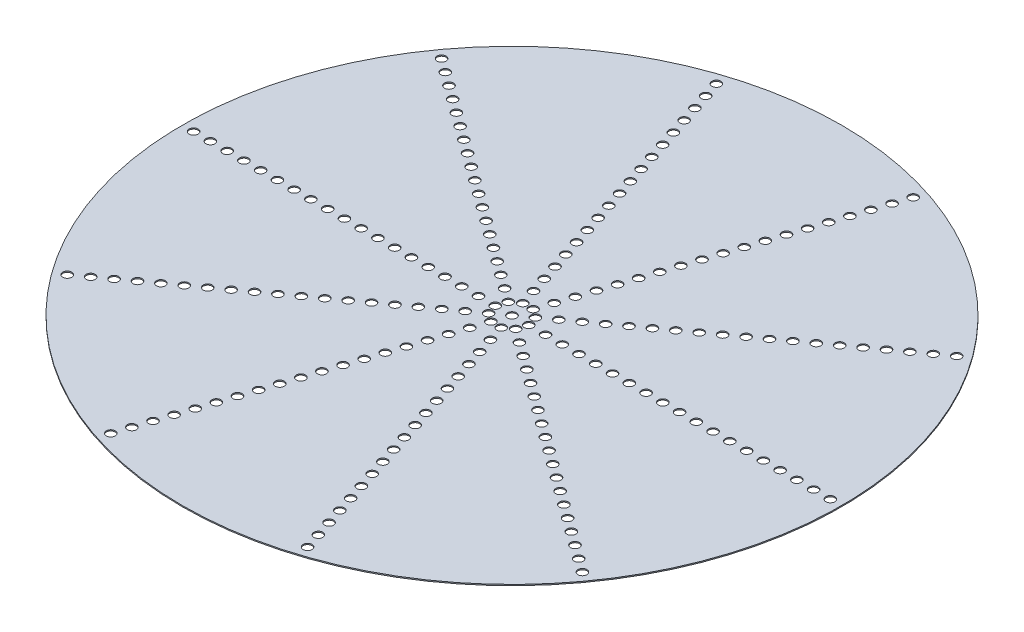
SolidWorks part; units mm, degrees
ref_plane "Front Plane" through (0, 0, 0) normal (0, 0, 1) x (1, 0, 0)
ref_plane "Top Plane" through (0, 0, 0) normal (0, 1, 0) x (1, 0, 0)
ref_plane "Right Plane" through (0, 0, 0) normal (1, 0, 0) x (0, 0, -1)
sketch "Croquis1" plane through (0, 0, 0) normal (0, 1, 0) x (1, 0, 0)
  circle A0 centre (0, 0) radius 29.5
  dimension "D1" = 59
extrude "Saliente-Extruir1" add sketch "Croquis1" along normal blind 0.1
sketch "Croquis2" plane through (0, 0.1, 0) normal (0, 1, 0) x (1, 0, 0)
  circle A0 centre (0, 0) radius 0.4
  circle A1 centre (1.5, 0) radius 0.4
  circle A2 centre (3, 0) radius 0.4
  circle A3 centre (4.5, 0) radius 0.4
  circle A4 centre (6, 0) radius 0.4
  circle A5 centre (7.5, 0) radius 0.4
  circle A6 centre (9, 0) radius 0.4
  circle A7 centre (10.5, 0) radius 0.4
  circle A8 centre (12, 0) radius 0.4
  circle A9 centre (13.5, 0) radius 0.4
  circle A10 centre (15, 0) radius 0.4
  circle A11 centre (16.5, 0) radius 0.4
  circle A12 centre (18, 0) radius 0.4
  circle A13 centre (19.5, 0) radius 0.4
  circle A14 centre (21, 0) radius 0.4
  circle A15 centre (22.5, 0) radius 0.4
  circle A16 centre (24, 0) radius 0.4
  circle A17 centre (25.5, 0) radius 0.4
  circle A18 centre (27, 0) radius 0.4
  circle A19 centre (28.5, 0) radius 0.4
  circle A20 centre (1.2135, -0.8817) radius 0.4
  circle A21 centre (2.4271, -1.7634) radius 0.4
  circle A22 centre (3.6406, -2.645) radius 0.4
  circle A23 centre (4.8541, -3.5267) radius 0.4
  circle A24 centre (6.0676, -4.4084) radius 0.4
  circle A25 centre (7.2812, -5.2901) radius 0.4
  circle A26 centre (8.4947, -6.1717) radius 0.4
  circle A27 centre (9.7082, -7.0534) radius 0.4
  circle A28 centre (10.9217, -7.9351) radius 0.4
  circle A29 centre (12.1353, -8.8168) radius 0.4
  circle A30 centre (13.3488, -9.6985) radius 0.4
  circle A31 centre (14.5623, -10.5801) radius 0.4
  circle A32 centre (15.7758, -11.4618) radius 0.4
  circle A33 centre (16.9894, -12.3435) radius 0.4
  circle A34 centre (18.2029, -13.2252) radius 0.4
  circle A35 centre (19.4164, -14.1068) radius 0.4
  circle A36 centre (20.6299, -14.9885) radius 0.4
  circle A37 centre (21.8435, -15.8702) radius 0.4
  circle A38 centre (23.057, -16.7519) radius 0.4
  circle A39 centre (0.4635, -1.4266) radius 0.4
  circle A40 centre (0.9271, -2.8532) radius 0.4
  circle A41 centre (1.3906, -4.2798) radius 0.4
  circle A42 centre (1.8541, -5.7063) radius 0.4
  circle A43 centre (2.3176, -7.1329) radius 0.4
  circle A44 centre (2.7812, -8.5595) radius 0.4
  circle A45 centre (3.2447, -9.9861) radius 0.4
  circle A46 centre (3.7082, -11.4127) radius 0.4
  circle A47 centre (4.1717, -12.8393) radius 0.4
  circle A48 centre (4.6353, -14.2658) radius 0.4
  circle A49 centre (5.0988, -15.6924) radius 0.4
  circle A50 centre (5.5623, -17.119) radius 0.4
  circle A51 centre (6.0258, -18.5456) radius 0.4
  circle A52 centre (6.4894, -19.9722) radius 0.4
  circle A53 centre (6.9529, -21.3988) radius 0.4
  circle A54 centre (7.4164, -22.8254) radius 0.4
  circle A55 centre (7.8799, -24.2519) radius 0.4
  circle A56 centre (8.3435, -25.6785) radius 0.4
  circle A57 centre (8.807, -27.1051) radius 0.4
  circle A58 centre (-0.4635, -1.4266) radius 0.4
  circle A59 centre (-0.9271, -2.8532) radius 0.4
  circle A60 centre (-1.3906, -4.2798) radius 0.4
  circle A61 centre (-1.8541, -5.7063) radius 0.4
  circle A62 centre (-2.3176, -7.1329) radius 0.4
  circle A63 centre (-2.7812, -8.5595) radius 0.4
  circle A64 centre (-3.2447, -9.9861) radius 0.4
  circle A65 centre (-3.7082, -11.4127) radius 0.4
  circle A66 centre (-4.1717, -12.8393) radius 0.4
  circle A67 centre (-4.6353, -14.2658) radius 0.4
  circle A68 centre (-5.0988, -15.6924) radius 0.4
  circle A69 centre (-5.5623, -17.119) radius 0.4
  circle A70 centre (-6.0258, -18.5456) radius 0.4
  circle A71 centre (-6.4894, -19.9722) radius 0.4
  circle A72 centre (-6.9529, -21.3988) radius 0.4
  circle A73 centre (-7.4164, -22.8254) radius 0.4
  circle A74 centre (-7.8799, -24.2519) radius 0.4
  circle A75 centre (-8.3435, -25.6785) radius 0.4
  circle A76 centre (-8.807, -27.1051) radius 0.4
  circle A77 centre (-1.2135, -0.8817) radius 0.4
  circle A78 centre (-2.4271, -1.7634) radius 0.4
  circle A79 centre (-3.6406, -2.645) radius 0.4
  circle A80 centre (-4.8541, -3.5267) radius 0.4
  circle A81 centre (-6.0676, -4.4084) radius 0.4
  circle A82 centre (-7.2812, -5.2901) radius 0.4
  circle A83 centre (-8.4947, -6.1717) radius 0.4
  circle A84 centre (-9.7082, -7.0534) radius 0.4
  circle A85 centre (-10.9217, -7.9351) radius 0.4
  circle A86 centre (-12.1353, -8.8168) radius 0.4
  circle A87 centre (-13.3488, -9.6985) radius 0.4
  circle A88 centre (-14.5623, -10.5801) radius 0.4
  circle A89 centre (-15.7758, -11.4618) radius 0.4
  circle A90 centre (-16.9894, -12.3435) radius 0.4
  circle A91 centre (-18.2029, -13.2252) radius 0.4
  circle A92 centre (-19.4164, -14.1068) radius 0.4
  circle A93 centre (-20.6299, -14.9885) radius 0.4
  circle A94 centre (-21.8435, -15.8702) radius 0.4
  circle A95 centre (-23.057, -16.7519) radius 0.4
  circle A96 centre (-1.5, 0) radius 0.4
  circle A97 centre (-3, 0) radius 0.4
  circle A98 centre (-4.5, 0) radius 0.4
  circle A99 centre (-6, 0) radius 0.4
  circle A100 centre (-7.5, 0) radius 0.4
  circle A101 centre (-9, 0) radius 0.4
  circle A102 centre (-10.5, 0) radius 0.4
  circle A103 centre (-12, 0) radius 0.4
  circle A104 centre (-13.5, 0) radius 0.4
  circle A105 centre (-15, 0) radius 0.4
  circle A106 centre (-16.5, 0) radius 0.4
  circle A107 centre (-18, 0) radius 0.4
  circle A108 centre (-19.5, 0) radius 0.4
  circle A109 centre (-21, 0) radius 0.4
  circle A110 centre (-22.5, 0) radius 0.4
  circle A111 centre (-24, 0) radius 0.4
  circle A112 centre (-25.5, 0) radius 0.4
  circle A113 centre (-27, 0) radius 0.4
  circle A114 centre (-28.5, 0) radius 0.4
  circle A115 centre (-1.2135, 0.8817) radius 0.4
  circle A116 centre (-2.4271, 1.7634) radius 0.4
  circle A117 centre (-3.6406, 2.645) radius 0.4
  circle A118 centre (-4.8541, 3.5267) radius 0.4
  circle A119 centre (-6.0676, 4.4084) radius 0.4
  circle A120 centre (-7.2812, 5.2901) radius 0.4
  circle A121 centre (-8.4947, 6.1717) radius 0.4
  circle A122 centre (-9.7082, 7.0534) radius 0.4
  circle A123 centre (-10.9217, 7.9351) radius 0.4
  circle A124 centre (-12.1353, 8.8168) radius 0.4
  circle A125 centre (-13.3488, 9.6985) radius 0.4
  circle A126 centre (-14.5623, 10.5801) radius 0.4
  circle A127 centre (-15.7758, 11.4618) radius 0.4
  circle A128 centre (-16.9894, 12.3435) radius 0.4
  circle A129 centre (-18.2029, 13.2252) radius 0.4
  circle A130 centre (-19.4164, 14.1068) radius 0.4
  circle A131 centre (-20.6299, 14.9885) radius 0.4
  circle A132 centre (-21.8435, 15.8702) radius 0.4
  circle A133 centre (-23.057, 16.7519) radius 0.4
  circle A134 centre (-0.4635, 1.4266) radius 0.4
  circle A135 centre (-0.9271, 2.8532) radius 0.4
  circle A136 centre (-1.3906, 4.2798) radius 0.4
  circle A137 centre (-1.8541, 5.7063) radius 0.4
  circle A138 centre (-2.3176, 7.1329) radius 0.4
  circle A139 centre (-2.7812, 8.5595) radius 0.4
  circle A140 centre (-3.2447, 9.9861) radius 0.4
  circle A141 centre (-3.7082, 11.4127) radius 0.4
  circle A142 centre (-4.1717, 12.8393) radius 0.4
  circle A143 centre (-4.6353, 14.2658) radius 0.4
  circle A144 centre (-5.0988, 15.6924) radius 0.4
  circle A145 centre (-5.5623, 17.119) radius 0.4
  circle A146 centre (-6.0258, 18.5456) radius 0.4
  circle A147 centre (-6.4894, 19.9722) radius 0.4
  circle A148 centre (-6.9529, 21.3988) radius 0.4
  circle A149 centre (-7.4164, 22.8254) radius 0.4
  circle A150 centre (-7.8799, 24.2519) radius 0.4
  circle A151 centre (-8.3435, 25.6785) radius 0.4
  circle A152 centre (-8.807, 27.1051) radius 0.4
  circle A153 centre (0.4635, 1.4266) radius 0.4
  circle A154 centre (0.9271, 2.8532) radius 0.4
  circle A155 centre (1.3906, 4.2798) radius 0.4
  circle A156 centre (1.8541, 5.7063) radius 0.4
  circle A157 centre (2.3176, 7.1329) radius 0.4
  circle A158 centre (2.7812, 8.5595) radius 0.4
  circle A159 centre (3.2447, 9.9861) radius 0.4
  circle A160 centre (3.7082, 11.4127) radius 0.4
  circle A161 centre (4.1717, 12.8393) radius 0.4
  circle A162 centre (4.6353, 14.2658) radius 0.4
  circle A163 centre (5.0988, 15.6924) radius 0.4
  circle A164 centre (5.5623, 17.119) radius 0.4
  circle A165 centre (6.0258, 18.5456) radius 0.4
  circle A166 centre (6.4894, 19.9722) radius 0.4
  circle A167 centre (6.9529, 21.3988) radius 0.4
  circle A168 centre (7.4164, 22.8254) radius 0.4
  circle A169 centre (7.8799, 24.2519) radius 0.4
  circle A170 centre (8.3435, 25.6785) radius 0.4
  circle A171 centre (8.807, 27.1051) radius 0.4
  circle A172 centre (1.2135, 0.8817) radius 0.4
  circle A173 centre (2.4271, 1.7634) radius 0.4
  circle A174 centre (3.6406, 2.645) radius 0.4
  circle A175 centre (4.8541, 3.5267) radius 0.4
  circle A176 centre (6.0676, 4.4084) radius 0.4
  circle A177 centre (7.2812, 5.2901) radius 0.4
  circle A178 centre (8.4947, 6.1717) radius 0.4
  circle A179 centre (9.7082, 7.0534) radius 0.4
  circle A180 centre (10.9217, 7.9351) radius 0.4
  circle A181 centre (12.1353, 8.8168) radius 0.4
  circle A182 centre (13.3488, 9.6985) radius 0.4
  circle A183 centre (14.5623, 10.5801) radius 0.4
  circle A184 centre (15.7758, 11.4618) radius 0.4
  circle A185 centre (16.9894, 12.3435) radius 0.4
  circle A186 centre (18.2029, 13.2252) radius 0.4
  circle A187 centre (19.4164, 14.1068) radius 0.4
  circle A188 centre (20.6299, 14.9885) radius 0.4
  circle A189 centre (21.8435, 15.8702) radius 0.4
  circle A190 centre (23.057, 16.7519) radius 0.4
  point P386 (0, 0)
  dimension "D1" = 0.8
  dimension "D2" = 20
  dimension "D3" = 10
extrude "Cortar-Extruir1" cut sketch "Croquis2" against normal through all
